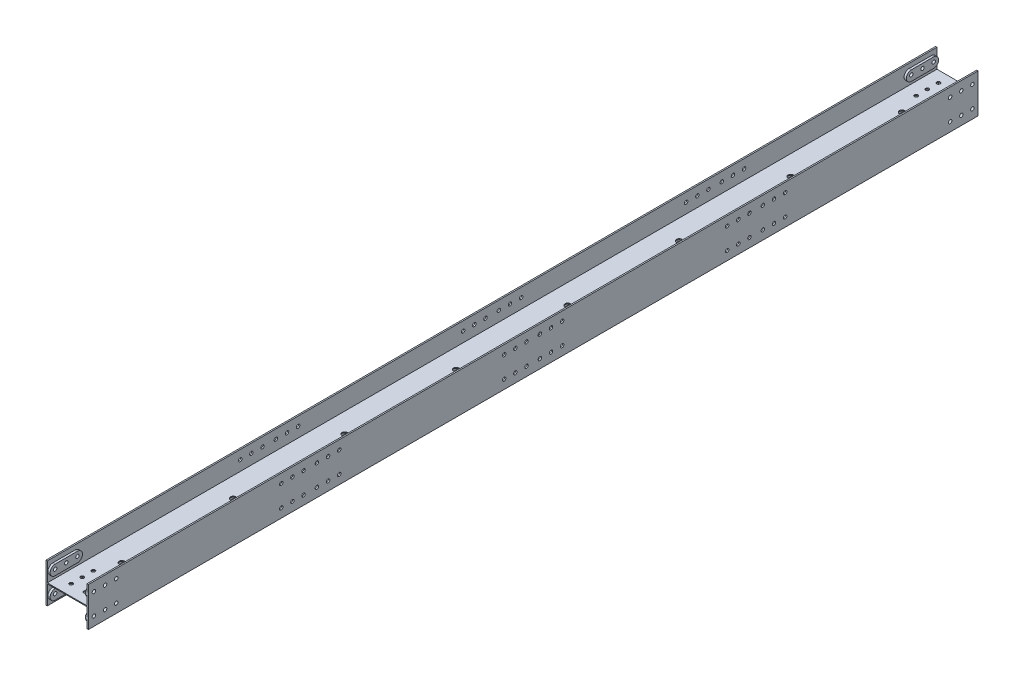
SolidWorks part; units mm, degrees
ref_plane "前视基准面" through (0, 0, 0) normal (0, 0, 1) x (1, 0, 0)
ref_plane "上视基准面" through (0, 0, 0) normal (0, 1, 0) x (1, 0, 0)
ref_plane "右视基准面" through (0, 0, 0) normal (1, 0, 0) x (0, 0, -1)
sketch "草图1" plane through (0, 0, 0) normal (0, 0, 1) x (1, 0, 0)
  line L0 (-1000, 0) -> (49000, 0) construction
  line L1 (0, -1000) -> (0, 49000) construction
  line L3 (-190, 175) -> (190, 175)
  line L4 (-190, 175) -> (-190, -175)
  line L5 (-190, -175) -> (190, -175)
  line L6 (190, 175) -> (190, -175)
  line L7 (-178, 175) -> (178, 175)
  line L8 (-178, 175) -> (-178, 4)
  line L9 (-178, 4) -> (178, 4)
  line L10 (178, 175) -> (178, 4)
  line L11 (-178, -4) -> (178, -4)
  line L12 (-178, -4) -> (-178, -175)
  line L13 (-178, -175) -> (178, -175)
  line L14 (178, -4) -> (178, -175)
  dimension "D1" = 380
  dimension "D2" = 350
  dimension "D3" = 190
  dimension "D4" = 175
  dimension "D5" = 4
  dimension "D6" = 8
  dimension "D7" = 12
  dimension "D8" = 12
extrude "拉伸1" add sketch "草图1" along normal blind 3990 contours L11 L14 L5 L6 L3 L10 L9 L8 L4 L12
sketch "草图2" plane through (190, 0, 0) normal (1, 0, 0) x (0, 0, -1)
  line L0 (-4990, 0) -> (45010, 0) construction
  line L1 (-3990, 175) -> (-3990, -175) construction
  line L2 (-3940, 95) -> (-3840, 95) construction
  line L3 (-3940, 95) -> (-3940, -95) construction
  line L4 (-3940, 95) -> (-2260, 95) construction
  line L5 (-2060, 95) -> (-1740, 95) construction
  line L6 (-1940, 95) -> (-260, 95) construction
  circle A0 centre (-3940, 95) radius 15.5
  circle A1 centre (-3840, 95) radius 15.5
  circle A2 centre (-3740, 95) radius 15.5
  circle A3 centre (-3940, -95) radius 15.5
  circle A4 centre (-3840, -95) radius 15.5
  circle A5 centre (-3740, -95) radius 15.5
  circle A6 centre (-2260, 95) radius 15.5
  circle A7 centre (-2160, 95) radius 15.5
  circle A8 centre (-2060, 95) radius 15.5
  circle A9 centre (-2260, -95) radius 15.5
  circle A10 centre (-2160, -95) radius 15.5
  circle A11 centre (-2060, -95) radius 15.5
  circle A12 centre (-1740, 95) radius 15.5
  circle A13 centre (-1940, 95) radius 15.5
  circle A14 centre (-1840, 95) radius 15.5
  circle A15 centre (-1940, -95) radius 15.5
  circle A16 centre (-1840, -95) radius 15.5
  circle A17 centre (-1740, -95) radius 15.5
  circle A18 centre (-260, 95) radius 15.5
  circle A19 centre (-60, 95) radius 15.5
  circle A20 centre (-60, -95) radius 15.5
  circle A21 centre (-160, 95) radius 15.5
  circle A22 centre (-160, -95) radius 15.5
  circle A23 centre (-260, -95) radius 15.5
  point P5 (-3990, 0)
  dimension "D1" = 31
  dimension "D2" = 50
  dimension "D3" = 95
  dimension "D4" = 100
  dimension "D5" = 100
  dimension "D6" = 190
  dimension "D7" = 1680
  dimension "D8" = 320
  dimension "D9" = 1680
sketch "草图3" plane through (-178, 0, 0) normal (1, 0, 0) x (0, 0, -1)
  line L0 (-4990, 89.5) -> (45010, 89.5) construction
  line L1 (-3990, 175) -> (-3990, 4) construction
  line L2 (-3940, 89.5) -> (-3740, 89.5) construction
  line L3 (-3940, 134.5) -> (-3740, 134.5)
  line L4 (-3940, 44.5) -> (-3740, 44.5)
  arc A0 (-3940, 134.5) -> (-3940, 44.5) centre (-3940, 89.5) ccw
  arc A1 (-3740, 44.5) -> (-3740, 134.5) centre (-3740, 89.5) ccw
  point P5 (-3990, 89.5)
  point P7 (-3840, 89.5)
  dimension "D1" = 90
  dimension "D2" = 200
  dimension "D3" = 50
extrude "拉伸2" add sketch "草图3" along normal blind 20
pattern_linear "阵列(线性)1" count 2 spacing 190 along (0, -1, 0) count 2 spacing 336 along (1, 0, 0) of "拉伸2"
extrude "拉伸3" cut sketch "草图2" against normal through all
mirror "镜向1" about plane through (0, 0, 0) normal (0, 0, 1) of bodies 105
sketch "草图4" plane through (0, 4, 0) normal (0, 1, 0) x (1, 0, 0)
  line L0 (0, 2990) -> (0, 52990) construction
  line L1 (-178, 3990) -> (178, 3990) construction
  line L2 (-822, 0) -> (49178, 0) construction
  line L3 (178, -3990) -> (178, 3990) construction
  line L4 (190, -3990) -> (190, 3990) construction
  line L5 (65, 3890) -> (-65, 3890) construction
  line L6 (65, 3890) -> (65, 3790) construction
  circle A0 centre (65, 3890) radius 15.5
  circle A1 centre (-65, 3890) radius 15.5
  circle A2 centre (65, 3790) radius 15.5
  circle A3 centre (-65, 3790) radius 15.5
  circle A4 centre (65, 3690) radius 15.5
  circle A5 centre (-65, 3690) radius 15.5
  circle A6 centre (0, 3500) radius 25
  circle A7 centre (0, 2500) radius 25
  circle A8 centre (0, 1500) radius 25
  circle A9 centre (0, 500) radius 25
  circle A10 centre (65, -3790) radius 15.5
  circle A11 centre (65, -3890) radius 15.5
  circle A12 centre (-65, -3890) radius 15.5
  circle A13 centre (-65, -3790) radius 15.5
  circle A14 centre (65, -3690) radius 15.5
  circle A15 centre (-65, -3690) radius 15.5
  circle A16 centre (0, -3500) radius 25
  circle A17 centre (0, -2500) radius 25
  circle A18 centre (0, -1500) radius 25
  circle A19 centre (0, -500) radius 25
  point P5 (0, 3990)
  point P10 (178, 0)
  dimension "D1" = 31
  dimension "D6" = 50
  dimension "D8" = 500
  dimension "D2" = 125
  dimension "D3" = 100
  dimension "D4" = 130
  dimension "D5" = 100
  dimension "D7" = 190
extrude "拉伸4" cut sketch "草图4" against normal through all
